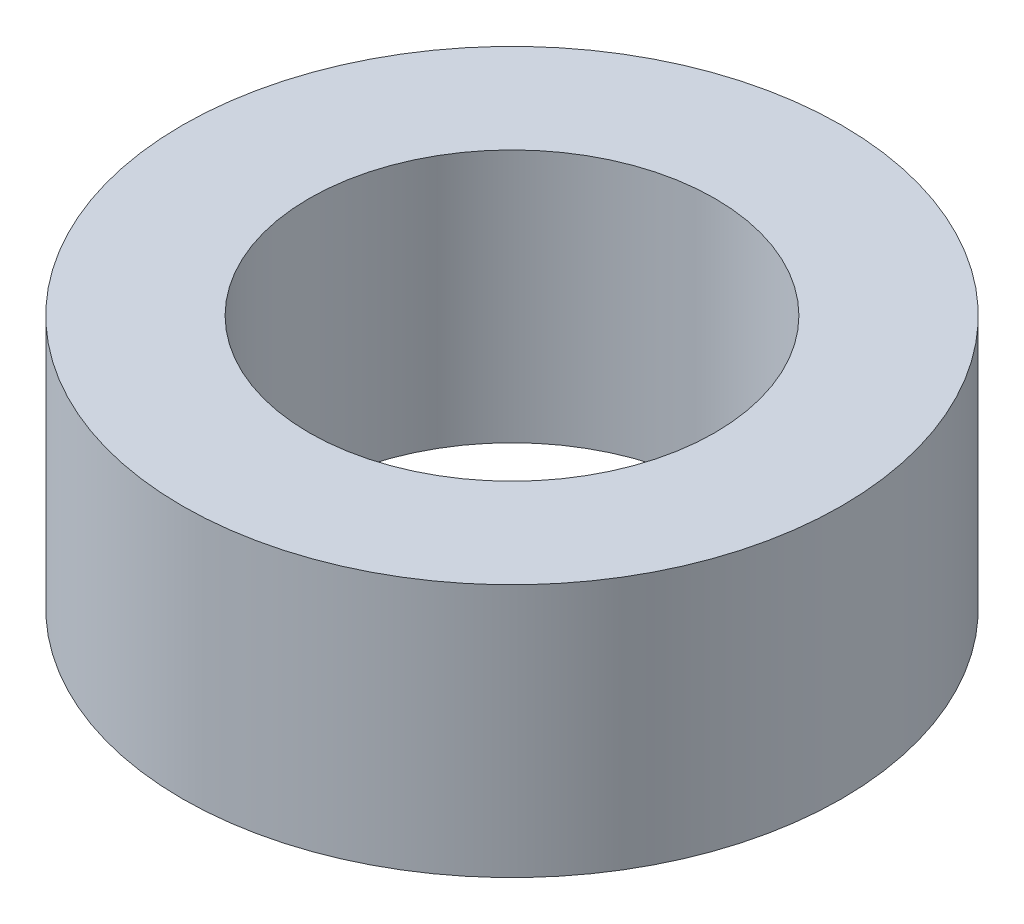
SolidWorks part; units mm, degrees
ref_plane "Front Plane" through (0, 0, 0) normal (0, 0, 1) x (1, 0, 0)
ref_plane "Top Plane" through (0, 0, 0) normal (0, 1, 0) x (1, 0, 0)
ref_plane "Right Plane" through (0, 0, 0) normal (1, 0, 0) x (0, 0, -1)
sketch "Sketch1" plane through (0, 0, 0) normal (0, 1, 0) x (1, 0, 0)
  circle A0 centre (0, 0) radius 4
  circle A1 centre (0, 0) radius 6.5
  dimension "D1" = 8
  dimension "D2" = 2.5
extrude "Boss-Extrude1" add sketch "Sketch1" along normal blind 5
